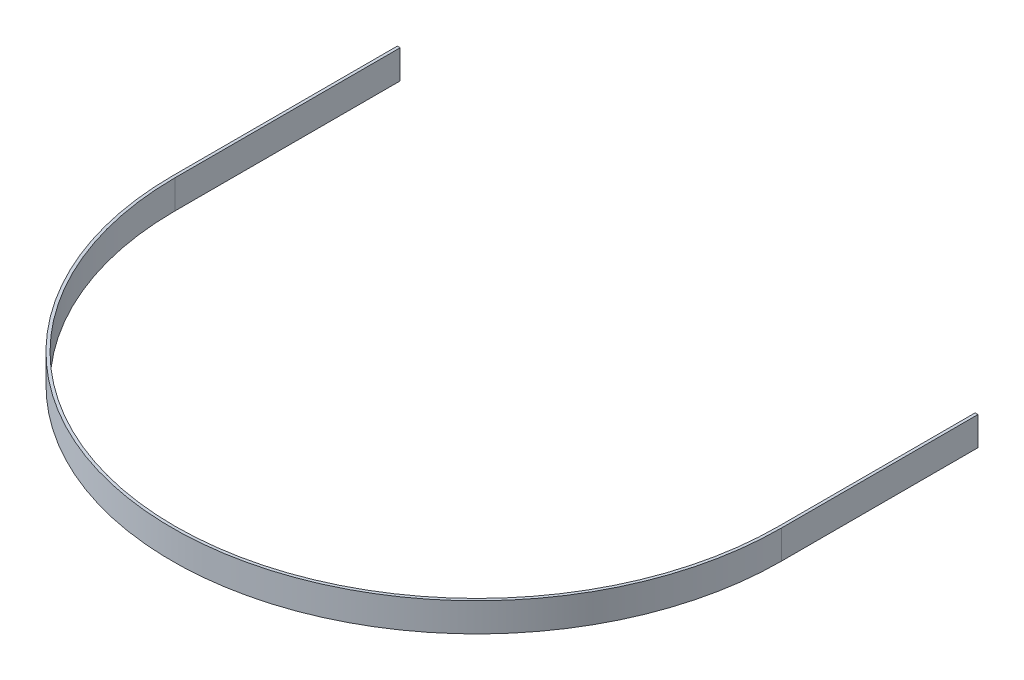
SolidWorks part; units mm, degrees
ref_plane "Front Plane" through (0, 0, 0) normal (0, 0, 1) x (1, 0, 0)
ref_plane "Top Plane" through (0, 0, 0) normal (0, 1, 0) x (1, 0, 0)
ref_plane "Right Plane" through (0, 0, 0) normal (1, 0, 0) x (0, 0, -1)
sketch "Sketch1" plane through (0, 0, 0) normal (0, 1, 0) x (1, 0, 0)
  line L0 (0, 23.2325) -> (0, -26.0028) construction
  line L1 (-27.7028, 0) -> (28.5842, 0) construction
  line L2 (-31.5, 0) -> (-31.5, -23.5)
  line L3 (31.5, -23.5) -> (31.5, -3)
  line L4 (-31.8, 0) -> (-31.8, -23.5)
  line L5 (31.8, -23.5) -> (31.8, -3)
  line L6 (-31.8, 0) -> (-31.5, 0)
  line L7 (31.5, -3) -> (31.8, -3)
  arc A0 (-31.8, -23.5) -> (31.8, -23.5) centre (0, -23.5) ccw
  arc A1 (-31.5, -23.5) -> (31.5, -23.5) centre (0, -23.5) ccw
  dimension "D2" = 31.5
  dimension "D1" = 3
  dimension "D3" = 63
  dimension "D4" = 23.5
  dimension "D5" = 20.5
  dimension "D6" = 31.5
  dimension "D7" = 0.3
extrude "Boss-Extrude1" add sketch "Sketch1" along normal blind 3
